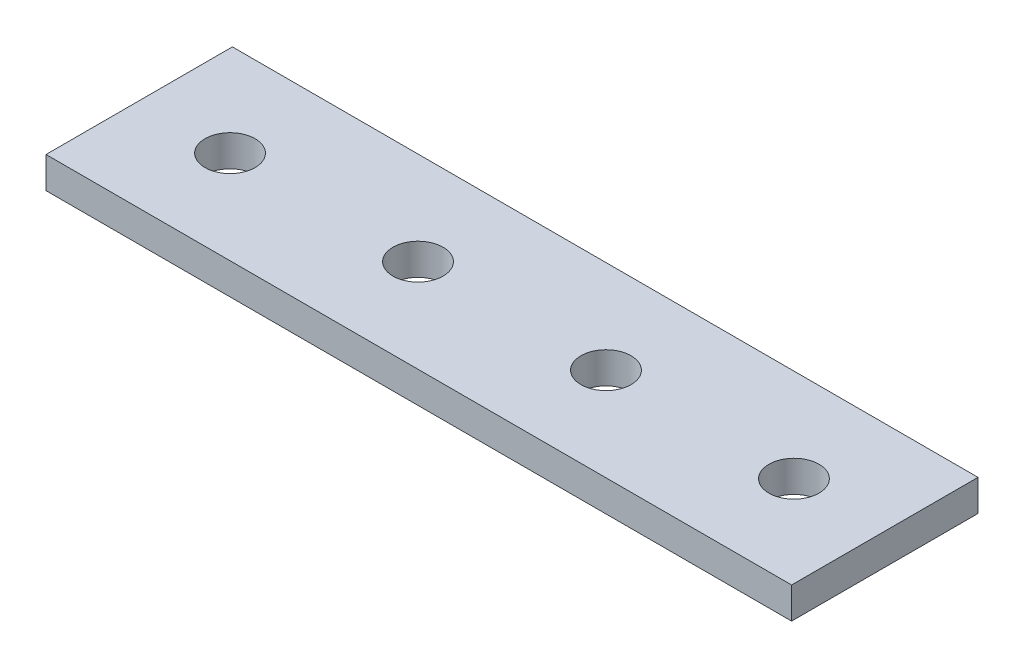
SolidWorks part; units mm, degrees
ref_plane "Front Plane" through (0, 0, 0) normal (0, 0, 1) x (1, 0, 0)
ref_plane "Top Plane" through (0, 0, 0) normal (0, 1, 0) x (1, 0, 0)
ref_plane "Right Plane" through (0, 0, 0) normal (1, 0, 0) x (0, 0, -1)
sketch "Sketch1" plane through (0, 0, 0) normal (0, 1, 0) x (1, 0, 0)
  line L0 (0, 5.95) -> (48, 5.95) construction
  line L1 (0, 0) -> (48, 0)
  line L2 (0, 0) -> (0, 11.9)
  line L3 (0, 11.9) -> (48, 11.9)
  line L4 (48, 0) -> (48, 11.9)
  line L5 (47.8, 11.9) -> (47.8, 0)
  line L6 (0.2, 11.9) -> (0.2, 0)
  point P7 (6, 5.95)
  point P8 (18, 5.95)
  point P9 (30, 5.95)
  point P10 (42, 5.95)
  dimension "D1" = 48
  dimension "D2" = 11.9
  dimension "D3" = 6
  dimension "D4" = 12
  dimension "D5" = 12
  dimension "D6" = 12
  dimension "D7" = 0.2
  dimension "D8" = 0.2
extrude "Boss-Extrude1" add sketch "Sketch1" along normal blind 2 contours L0 L6 L1 L5 | L6 L0 L5 L3
sketch "Sketch2" plane through (0, 2, 0) normal (0, 1, 0) x (1, 0, 0)
  point P0 (42, 5.95)
  point P2 (30, 5.95)
  point P4 (18, 5.95)
  point P6 (6, 5.95)
hole_wizard "M3 Clearance Hole1" positions "Sketch2" profile "Sketch3" hole size "M3" standard "ANSI Metric"
sketch "Sketch3" plane through (42, 2, -5.95) normal (1, 0, 0) x (0, 0, 1)
  line L0 (0, 0) -> (0, 3)
  line L1 (0, 3) -> (1.6, 3)
  line L2 (1.6, 3) -> (1.6, 0)
  line L5 (1.6, 0) -> (0, 0)
  line L10 (0, 3) -> (-1.6, 3) construction
  line L11 (0, -6.35) -> (0, 107.95) construction
  dimension "Hole Dia." = 3.2
  dimension "Hole Depth" = 3
  dimension "Drill Angle" = 180
